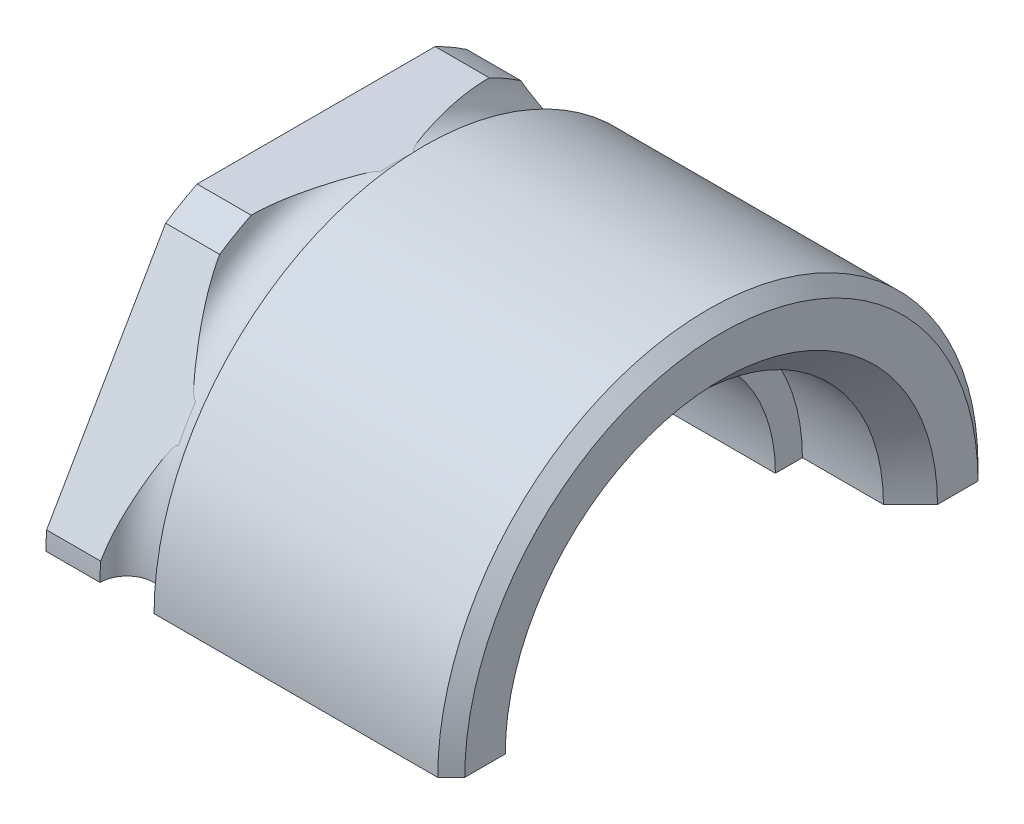
SolidWorks part; units mm, degrees
ref_plane "Face" through (0, 0, 0) normal (0, 0, 1) x (1, 0, 0)
ref_plane "Dessus" through (0, 0, 0) normal (0, 1, 0) x (1, 0, 0)
ref_plane "Droite" through (0, 0, 0) normal (1, 0, 0) x (0, 0, -1)
sketch "Esquisse1" plane through (0, 0, 0) normal (0, 0, 1) x (1, 0, 0)
  line L0 (-10, 0) -> (40, 0) construction
  line L1 (0, 12) -> (0, 20)
  line L2 (0, 20) -> (4, 20)
  line L3 (30, 19) -> (30, 16)
  line L4 (8, 20) -> (29, 20)
  line L5 (0, 12) -> (22, 12)
  line L6 (22, 12) -> (22, 14)
  line L7 (22, 14) -> (28, 14)
  line L8 (28, 14) -> (30, 16)
  line L9 (30, 19) -> (29, 20)
  arc A0 (4, 20) -> (8, 20) centre (6, 20) ccw
revolve "Base-Révolution" add sketch "Esquisse1" angle 360 about L0
sketch "Esquisse3" plane through (0, 0, 0) normal (-1, 0, 0) x (0, 0, 1)
  line L0 (-20.7321, 0) -> (-10.366, 17.9545)
  line L1 (0, 0) -> (25, 0) construction
  line L2 (0, 0) -> (0, 21) construction
  line L3 (-20.7321, 0) -> (-10.366, -17.9545)
  line L4 (20.7321, 0) -> (10.366, 17.9545)
  line L5 (20.7321, 0) -> (10.366, -17.9545)
  line L6 (0, 0) -> (12.3491, 21.3892) construction
  line L7 (-10.366, 17.9545) -> (10.366, 17.9545)
  line L8 (-10.366, -17.9545) -> (10.366, -17.9545)
  line L9 (0, 0) -> (-27, 0) construction
  circle A1 centre (0, 0) radius 23.8537
  dimension "D1" = 60
  dimension "D2" = 60
extrude "Enlèv. mat.-Extru.2" cut sketch "Esquisse3" against normal blind 6
sketch "Esquisse4" plane through (0, 0, 0) normal (0, 1, 0) x (1, 0, 0)
  line L1 (-10, -46) -> (50, -46)
  line L2 (-10, -46) -> (-10, 38)
  line L3 (-10, 38) -> (50, 38)
  line L4 (50, -46) -> (50, 38)
extrude "Enlèv. mat.-Extru.3" cut sketch "Esquisse4" against normal through all
